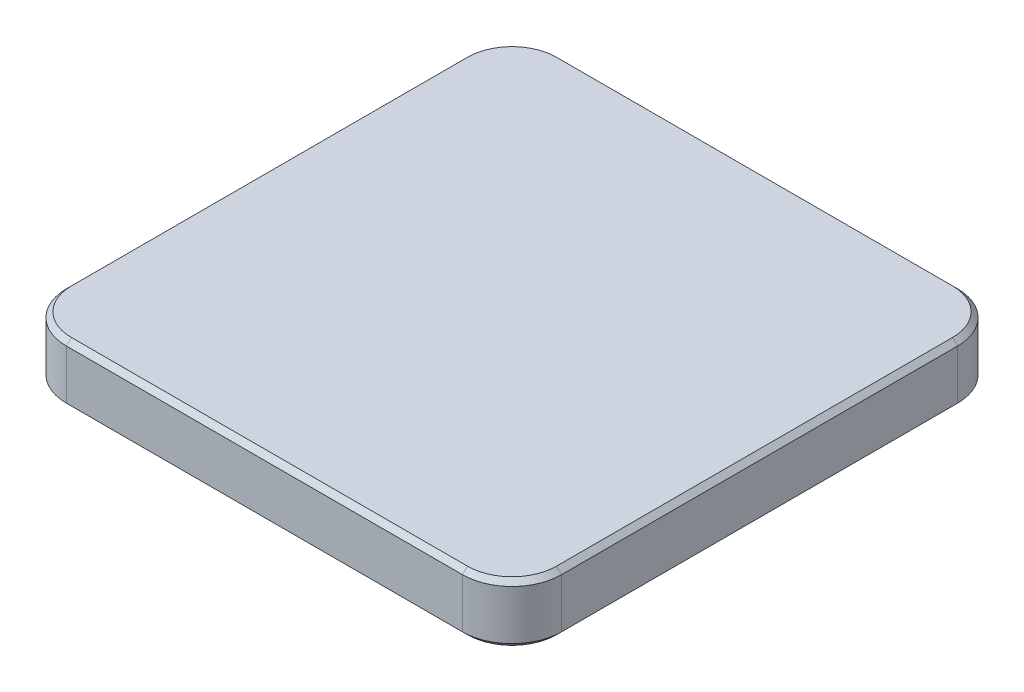
SolidWorks part; units mm, degrees
ref_plane "前基準面" through (0, 0, 0) normal (0, 0, 1) x (1, 0, 0)
ref_plane "上基準面" through (0, 0, 0) normal (0, 1, 0) x (1, 0, 0)
ref_plane "右基準面" through (0, 0, 0) normal (1, 0, 0) x (0, 0, -1)
sketch "草圖1" plane through (0, 0, 0) normal (0, 1, 0) x (1, 0, 0)
  line L1 (0, 0) -> (100, 0)
  line L2 (0, 0) -> (0, 100)
  line L3 (0, 100) -> (100, 100)
  line L4 (100, 0) -> (100, 100)
  dimension "D1" = 100
  dimension "D2" = 100
extrude "填料-伸長1" add sketch "草圖1" along normal blind 12
fillet "圓角1" radius 10 4 edges at (0, 6, -100) (100, 6, -100) (100, 6, 0) (0, 6, 0)
chamfer "導角1" distance 1 angle 45 16 edges at (2.9289, 0, -2.9289) (50, 0, 0) (97.0711, 0, -2.9289) (100, 0, -50) (97.0711, 0, -97.0711) (50, 0, -100) (2.9289, 0, -97.0711) (0, 0, -50) (97.0711, 12, -97.0711) (100, 12, -50) (97.0711, 12, -2.9289) (50, 12, 0) (2.9289, 12, -2.9289) (0, 12, -50) (2.9289, 12, -97.0711) (50, 12, -100)
